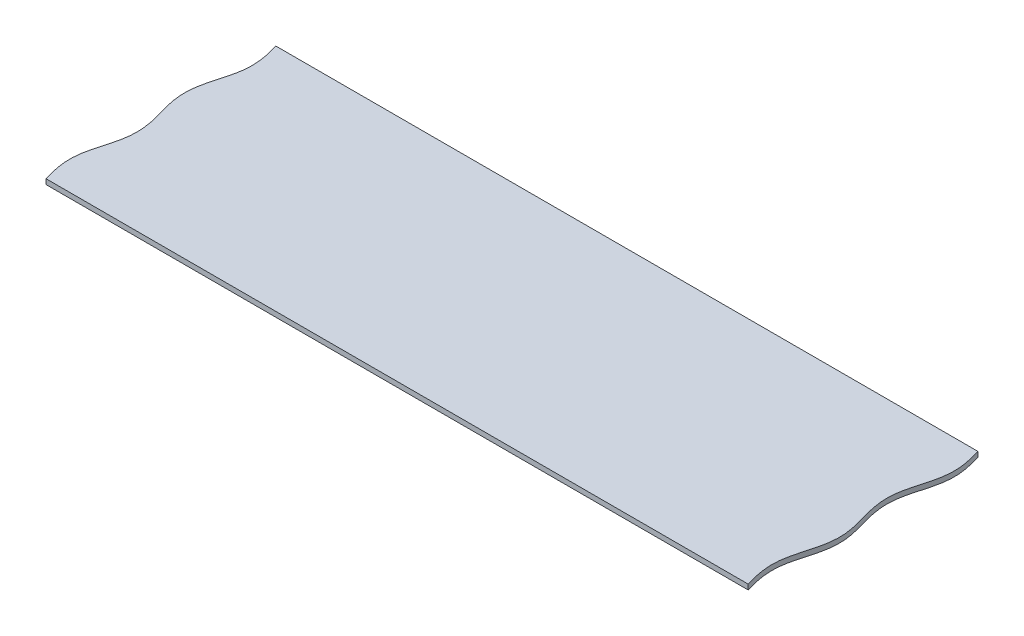
SolidWorks part; units mm, degrees
ref_plane "Front Plane" through (0, 0, 0) normal (0, 0, 1) x (1, 0, 0)
ref_plane "Top Plane" through (0, 0, 0) normal (0, 1, 0) x (1, 0, 0)
ref_plane "Right Plane" through (0, 0, 0) normal (1, 0, 0) x (0, 0, -1)
sketch "Sketch1" plane through (0, 0, 0) normal (0, 1, 0) x (1, 0, 0)
  line L0 (0, 0) -> (55, 0)
  line L2 (55, -18) -> (0, -18)
  spline S0 degree 4 poles (-0.3792, 1.7828) (-0.3712, 1.6982) (-0.3525, 1.5307) (-0.3202, 1.3049) (-0.2529, 0.9747) (-0.1846, 0.6715) (-0.0283, 0.096) (0.0309, -0.1051) (0.1898, -0.691) (0.2579, -0.9977) (0.3257, -1.3363) (0.3689, -1.6489) (0.3989, -1.9945) (0.4039, -2.3311) (0.3876, -2.6724) (0.3445, -3.0512) (0.2696, -3.4693) (0.1512, -3.9642) (-0.0096, -4.536) (-0.1829, -5.1507) (-0.3325, -5.8163) (-0.4124, -6.495) (-0.3996, -7.2231) (-0.2579, -8.1087) (0.0025, -9.0079) (0.2617, -9.9075) (0.4013, -10.7905) (0.4129, -11.5139) (0.3327, -12.1901) (0.1836, -12.853) (0.0112, -13.4651) (-0.1494, -14.0362) (-0.268, -14.5306) (-0.343, -14.9487) (-0.3864, -15.3275) (-0.4029, -15.6688) (-0.3981, -16.0054) (-0.3683, -16.351) (-0.3254, -16.6636) (-0.2577, -17.0022) (-0.1897, -17.309) (-0.0309, -17.8949) (0.0283, -18.0961) (0.1846, -18.6715) (0.2531, -18.9747) (0.3206, -19.3049) (0.353, -19.5307) (0.3718, -19.6982) (0.3798, -19.7828) knots 0 0 0 0 0 0.015175 0.030349 0.043501 0.056652 0.082955 0.109919 0.1234 0.136882 0.152331 0.16778 0.183228 0.198677 0.214125 0.229574 0.252676 0.275777 0.306674 0.337572 0.368827 0.399724 0.430621 0.469601 0.531395 0.569874 0.600771 0.631669 0.662566 0.693392 0.724218 0.747319 0.770421 0.785869 0.801318 0.816767 0.832215 0.847664 0.863112 0.876594 0.890076 0.91704 0.943344 0.956497 0.969649 0.984824 1 1 1 1 1 construction
  spline S1 degree 4 poles (0, 0) (0.0333, -0.1191) (0.083, -0.2972) (0.1898, -0.691) (0.2579, -0.9977) (0.3257, -1.3363) (0.3689, -1.6489) (0.3989, -1.9945) (0.4039, -2.3311) (0.3876, -2.6724) (0.3445, -3.0512) (0.2696, -3.4693) (0.1512, -3.9642) (-0.0096, -4.536) (-0.1829, -5.1507) (-0.3325, -5.8163) (-0.4124, -6.495) (-0.3996, -7.2231) (-0.2579, -8.1087) (0.0025, -9.0079) (0.2617, -9.9075) (0.4013, -10.7905) (0.4129, -11.5139) (0.3327, -12.1901) (0.1836, -12.853) (0.0112, -13.4651) (-0.1494, -14.0362) (-0.268, -14.5306) (-0.343, -14.9487) (-0.3864, -15.3275) (-0.4029, -15.6688) (-0.3981, -16.0054) (-0.3683, -16.351) (-0.3254, -16.6636) (-0.2577, -17.0022) (-0.1897, -17.309) (-0.083, -17.7028) (-0.0333, -17.8809) (0, -18) knots 0.082955 0.082955 0.082955 0.082955 0.082955 0.109919 0.1234 0.136882 0.152331 0.16778 0.183228 0.198677 0.214125 0.229574 0.252676 0.275777 0.306674 0.337572 0.368827 0.399724 0.430621 0.469601 0.531395 0.569874 0.600771 0.631669 0.662566 0.693392 0.724218 0.747319 0.770421 0.785869 0.801318 0.816767 0.832215 0.847664 0.863112 0.876594 0.890076 0.91704 0.91704 0.91704 0.91704 0.91704
  spline S2 degree 4 poles (54.6208, 1.7828) (54.6288, 1.6982) (54.6475, 1.5307) (54.6798, 1.3049) (54.7471, 0.9747) (54.8154, 0.6715) (54.9717, 0.096) (55.0309, -0.1051) (55.1898, -0.691) (55.2579, -0.9977) (55.3257, -1.3363) (55.3689, -1.6489) (55.3989, -1.9945) (55.4039, -2.3311) (55.3876, -2.6724) (55.3445, -3.0512) (55.2696, -3.4693) (55.1512, -3.9642) (54.9904, -4.536) (54.8171, -5.1507) (54.6675, -5.8163) (54.5876, -6.495) (54.6004, -7.2231) (54.7421, -8.1087) (55.0025, -9.0079) (55.2617, -9.9075) (55.4013, -10.7905) (55.4129, -11.5139) (55.3327, -12.1901) (55.1836, -12.853) (55.0112, -13.4651) (54.8506, -14.0362) (54.732, -14.5306) (54.657, -14.9487) (54.6136, -15.3275) (54.5971, -15.6688) (54.6019, -16.0054) (54.6317, -16.351) (54.6746, -16.6636) (54.7423, -17.0022) (54.8103, -17.309) (54.9691, -17.8949) (55.0283, -18.0961) (55.1846, -18.6715) (55.2531, -18.9747) (55.3206, -19.3049) (55.353, -19.5307) (55.3718, -19.6982) (55.3798, -19.7828) knots 0 0 0 0 0 0.015175 0.030349 0.043501 0.056652 0.082955 0.109919 0.1234 0.136882 0.152331 0.16778 0.183228 0.198677 0.214125 0.229574 0.252676 0.275777 0.306674 0.337572 0.368827 0.399724 0.430621 0.469601 0.531395 0.569874 0.600771 0.631669 0.662566 0.693392 0.724218 0.747319 0.770421 0.785869 0.801318 0.816767 0.832215 0.847664 0.863112 0.876594 0.890076 0.91704 0.943344 0.956497 0.969649 0.984824 1 1 1 1 1 construction
  spline S3 degree 4 poles (55, 0) (55.0333, -0.1191) (55.083, -0.2972) (55.1898, -0.691) (55.2579, -0.9977) (55.3257, -1.3363) (55.3689, -1.6489) (55.3989, -1.9945) (55.4039, -2.3311) (55.3876, -2.6724) (55.3445, -3.0512) (55.2696, -3.4693) (55.1512, -3.9642) (54.9904, -4.536) (54.8171, -5.1507) (54.6675, -5.8163) (54.5876, -6.495) (54.6004, -7.2231) (54.7421, -8.1087) (55.0025, -9.0079) (55.2617, -9.9075) (55.4013, -10.7905) (55.4129, -11.5139) (55.3327, -12.1901) (55.1836, -12.853) (55.0112, -13.4651) (54.8506, -14.0362) (54.732, -14.5306) (54.657, -14.9487) (54.6136, -15.3275) (54.5971, -15.6688) (54.6019, -16.0054) (54.6317, -16.351) (54.6746, -16.6636) (54.7423, -17.0022) (54.8103, -17.309) (54.917, -17.7028) (54.9667, -17.8809) (55, -18) knots 0.082955 0.082955 0.082955 0.082955 0.082955 0.109919 0.1234 0.136882 0.152331 0.16778 0.183228 0.198677 0.214125 0.229574 0.252676 0.275777 0.306674 0.337572 0.368827 0.399724 0.430621 0.469601 0.531395 0.569874 0.600771 0.631669 0.662566 0.693392 0.724218 0.747319 0.770421 0.785869 0.801318 0.816767 0.832215 0.847664 0.863112 0.876594 0.890076 0.91704 0.91704 0.91704 0.91704 0.91704
  point P3 (55, -0.3308)
  point P4 (55, -18.3322)
  point P5 (55.0896, -18)
  dimension "D4" = 18
  dimension "D5" = 55
extrude "Boss-Extrude1" add sketch "Sketch1" along normal blind 0.4
